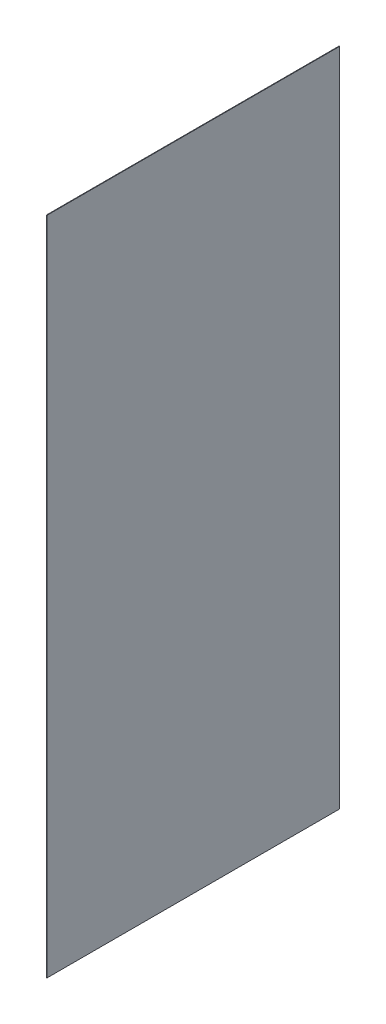
SolidWorks part; units mm, degrees
ref_plane "Front Plane" through (0, 0, 0) normal (0, 0, 1) x (1, 0, 0)
ref_plane "Top Plane" through (0, 0, 0) normal (0, 1, 0) x (1, 0, 0)
ref_plane "Right Plane" through (0, 0, 0) normal (1, 0, 0) x (0, 0, -1)
other "Configuration Table"
sketch "Sketch1" plane through (0, 0, 0) normal (0, 0, 1) x (1, 0, 0)
  line L1 (698.5, 120) -> (700, 120)
  line L2 (698.5, 120) -> (698.5, 1970)
  line L3 (698.5, 1970) -> (700, 1970)
  line L4 (700, 120) -> (700, 1970)
extrude "PACK_dis_yan_sag_1" add sketch "Sketch1" against normal blind 820 separate body
